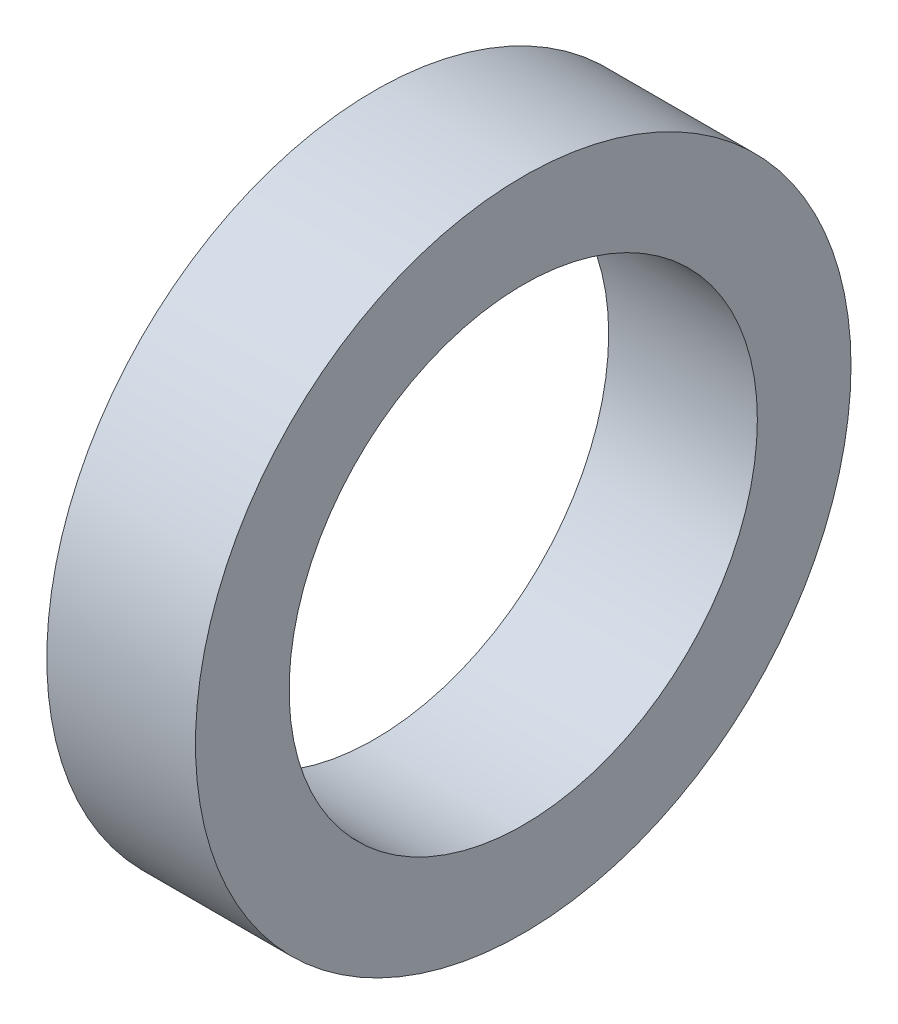
SolidWorks part; units mm, degrees
ref_plane "Front Plane" through (0, 0, 0) normal (0, 0, 1) x (1, 0, 0)
ref_plane "Top Plane" through (0, 0, 0) normal (0, 1, 0) x (1, 0, 0)
ref_plane "Right Plane" through (0, 0, 0) normal (1, 0, 0) x (0, 0, -1)
sketch "Sketch1" plane through (0, 0, 0) normal (1, 0, 0) x (0, 0, -1)
  circle A0 centre (0, 0) radius 2.5
  circle A1 centre (0, 0) radius 3.5
  dimension "D1" = 5
  dimension "D2" = 7
extrude "Boss-Extrude1" add sketch "Sketch1" along normal blind 1.5875
